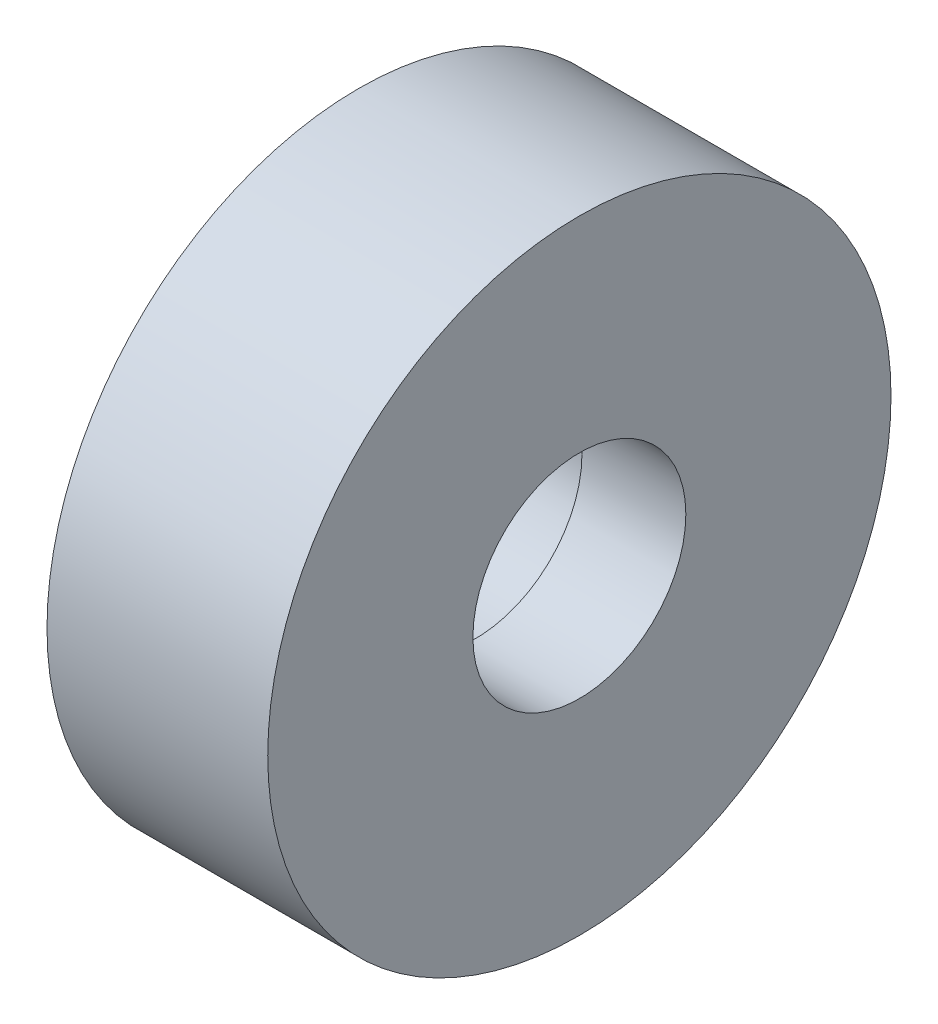
SolidWorks part; units mm, degrees
ref_plane "Front Plane" through (0, 0, 0) normal (0, 0, 1) x (1, 0, 0)
ref_plane "Top Plane" through (0, 0, 0) normal (0, 1, 0) x (1, 0, 0)
ref_plane "Right Plane" through (0, 0, 0) normal (1, 0, 0) x (0, 0, -1)
sketch "Sketch1" plane through (0, 0, 0) normal (0, 0, 1) x (1, 0, 0)
  line L0 (0, 0) -> (5.1881, 0) construction
  line L2 (-4.25, 1.125) -> (-4.25, 12) construction
  line L3 (-4.25, 12) -> (4.25, 12)
  line L4 (4.25, 4.1) -> (4.25, 12)
  line L5 (-4.25, 12) -> (-4.25, 4.15)
  line L6 (-4.25, 4.15) -> (0.25, 4.15)
  line L8 (0.25, 4.1) -> (4.25, 4.1)
  line L11 (0.25, 4.15) -> (0.25, 4.1)
  dimension "D1" = 12
  dimension "D2" = 8.5
  dimension "D3" = 4.15
  dimension "D4" = 4.25
  dimension "D5" = 4.1
  dimension "D6" = 4
revolve "Revolve1" add sketch "Sketch1" angle 360 about L0
